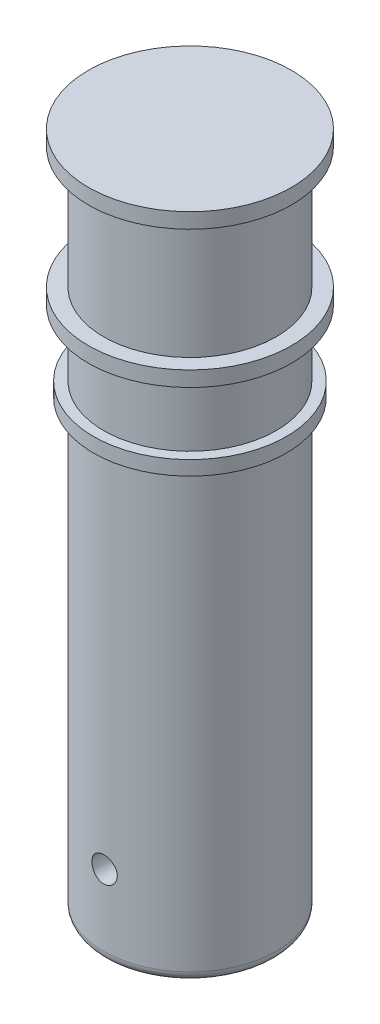
SolidWorks part; units mm, degrees
material "ABS"
ref_plane "Front Plane" through (0, 0, 0) normal (0, 0, 1) x (1, 0, 0)
ref_plane "Top Plane" through (0, 0, 0) normal (0, 1, 0) x (1, 0, 0)
ref_plane "Right Plane" through (0, 0, 0) normal (1, 0, 0) x (0, 0, -1)
sketch "Sketch1" plane through (0, 0, 0) normal (0, 0, 1) x (1, 0, 0)
  line L2 (-8.5, -51.915) -> (-8.5, -7.915)
  line L3 (-8.5, 0) -> (-10, 0)
  line L4 (-10, 0) -> (-10, 1.5)
  line L5 (-10, 1.5) -> (-8.5, 1.5)
  line L6 (-8.5, 1.5) -> (-8.5, 13.5)
  line L7 (-8.5, 13.5) -> (-10, 13.5)
  line L8 (-10, 13.5) -> (-10, 15)
  line L9 (-10, 15) -> (0, 15)
  line L10 (0, 15) -> (0, -37.915)
  line L11 (-4, -51.915) -> (-8.5, -51.915)
  line L12 (-4, -37.915) -> (-4, -51.915)
  line L13 (0, -37.915) -> (-4, -37.915)
  line L14 (-8.5, -7.915) -> (-9.5, -7.915)
  line L16 (-9.5, -7.915) -> (-9.5, -6.5)
  line L17 (-9.5, -6.5) -> (-8.5, -6.5)
  line L18 (-8.5, -6.5) -> (-8.5, 0)
  dimension "D1" = 8.5
  dimension "D2" = 1.5
  dimension "D3" = 51.915
  dimension "D4" = 1.5
  dimension "D5" = 4
  dimension "D6" = 14
  dimension "D7" = 15
  dimension "D8" = 10
  dimension "D9" = 44
  dimension "D10" = 1
  dimension "6.5" = 6.5
revolve "Revolve1" add sketch "Sketch1" angle 360 about L10
fillet "Fillet1" radius 1 2 edges at (-8.5, -51.915, 0) (-4, -51.915, 0)
hole_wizard "M3x0.5 Tapped Hole1" positions "Sketch2" profile "Sketch3" tap size "M3x0.5" standard "ANSI Metric"
sketch "Sketch2" plane through (0, 0, 0) normal (0, 0, 1) x (1, 0, 0)
  line L0 (-7.5, -51.915) -> (7.5, -51.915) construction
  point P0 (0, -43.915)
  dimension "D1" = 8
sketch "Sketch3" plane through (0, -43.915, 0) normal (1, 0, 0) x (0, 1, 0)
  line L0 (0, 0) -> (0, 8.5)
  line L1 (0, 8.5) -> (1.25, 8.5)
  line L2 (1.25, 8.5) -> (1.25, 0)
  line L5 (1.25, 0) -> (0, 0)
  line L11 (0, -6.35) -> (0, 107.95) construction
  dimension "Thru Tap Drill Dia." = 2.5
  dimension "Thru Tap Drill Depth" = 8.5
cosmetic thread "Hole Thread1" parameters "D2"=3
